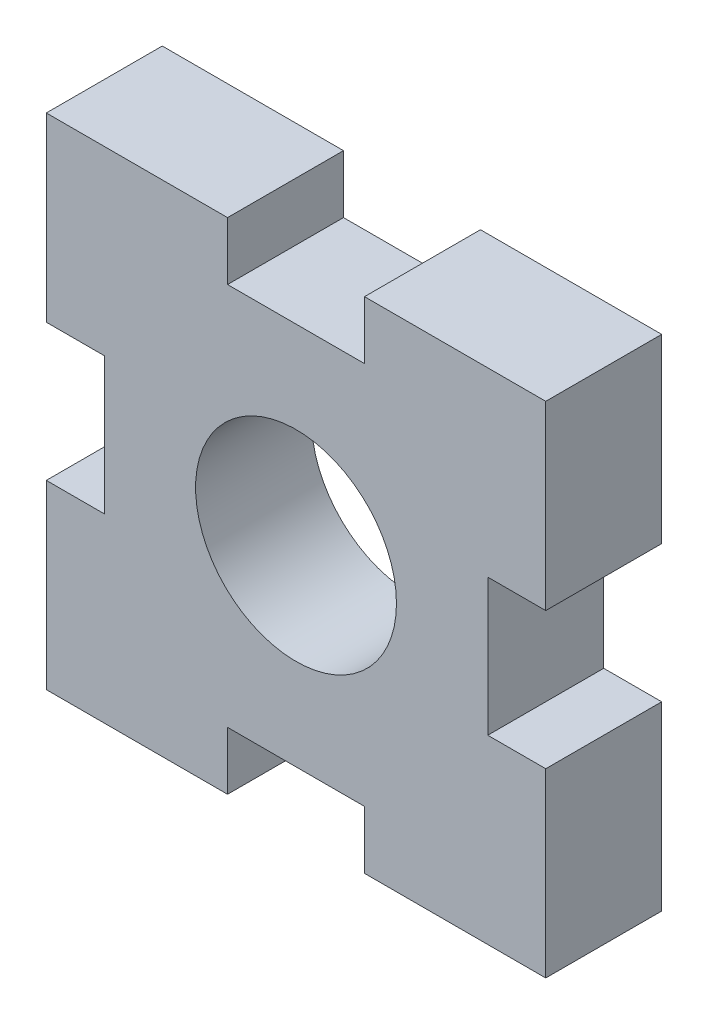
SolidWorks part; units mm, degrees
ref_plane "Front Plane" through (0, 0, 0) normal (0, 0, 1) x (1, 0, 0)
ref_plane "Top Plane" through (0, 0, 0) normal (0, 1, 0) x (1, 0, 0)
ref_plane "Right Plane" through (0, 0, 0) normal (1, 0, 0) x (0, 0, -1)
sketch "Sketch1" plane through (0, 0, 0) normal (0, 0, 1) x (1, 0, 0)
  line L1 (27.35, -27.35) -> (-27.35, -27.35)
  line L2 (27.35, -27.35) -> (27.35, 27.35)
  line L3 (27.35, 27.35) -> (-27.35, 27.35)
  line L4 (-27.35, -27.35) -> (-27.35, 27.35)
  line L5 (27.35, -27.35) -> (-27.35, 27.35) construction
  line L6 (27.35, 27.35) -> (-27.35, -27.35) construction
  point P0 (0, 0)
  dimension "D1" = 54.7
extrude "Boss-Extrude1" add sketch "Sketch1" along normal blind 12.7
sketch "Sketch2" plane through (0, 0, 12.7) normal (0, 0, 1) x (1, 0, 0)
  line L0 (27.35, 27.35) -> (-27.35, 27.35) construction
  line L1 (-7.5, 27.35) -> (7.5, 27.35)
  line L2 (-7.5, 27.35) -> (-7.5, 21)
  line L3 (-7.5, 21) -> (7.5, 21)
  line L4 (7.5, 27.35) -> (7.5, 21)
  point P6 (0, 21)
  dimension "D1" = 6.35
  dimension "D2" = 15
extrude "Cut-Extrude1" cut sketch "Sketch2" against normal through all
sketch "Sketch3" plane through (0, 0, 12.7) normal (0, 0, 1) x (1, 0, 0)
  circle A0 centre (0, 0) radius 11
  dimension "D1" = 22
extrude "Cut-Extrude2" cut sketch "Sketch3" against normal through all
pattern_circular "CirPattern1" count 4 over 360 about axis through (0, 0, 0) along (0, 0, 1) of "Cut-Extrude1"
